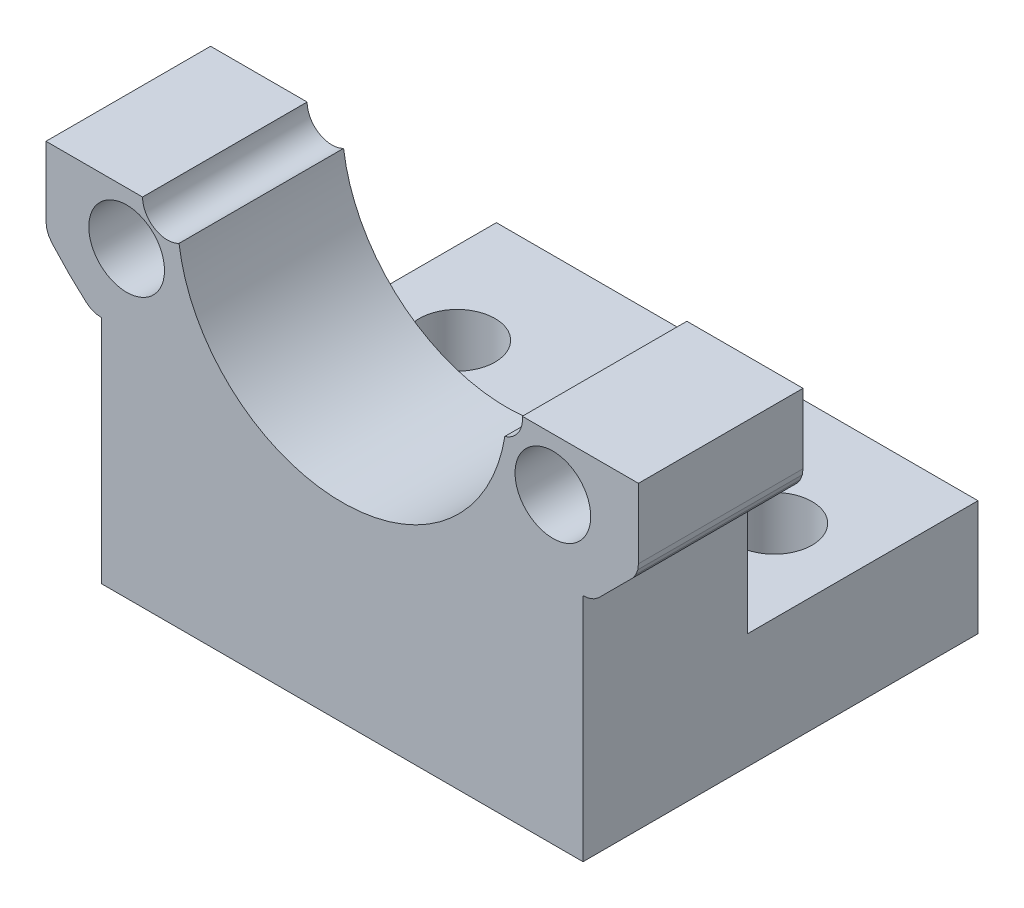
SolidWorks part; units mm, degrees
ref_plane "Front Plane" through (0, 0, 0) normal (0, 0, 1) x (1, 0, 0)
ref_plane "Top Plane" through (0, 0, 0) normal (0, 1, 0) x (1, 0, 0)
ref_plane "Right Plane" through (0, 0, 0) normal (1, 0, 0) x (0, 0, -1)
sketch "Sketch1" plane through (0, 0, 0) normal (0, 0, 1) x (1, 0, 0)
  line L1 (189.1991, 129.3361) -> (189.2194, 129.1684)
  line L2 (189.2194, 129.1684) -> (189.2766, 129.015)
  line L3 (189.2766, 129.015) -> (189.3751, 128.8705)
  line L4 (189.3751, 128.8705) -> (189.8798, 128.3332)
  line L5 (189.8798, 128.3332) -> (190.4171, 127.8285)
  line L6 (190.4171, 127.8285) -> (190.5582, 127.7318)
  line L7 (190.5582, 127.7318) -> (190.7157, 127.6726)
  line L8 (190.7157, 127.6726) -> (190.8827, 127.6526)
  line L9 (190.8827, 127.6526) -> (205.5156, 127.6526)
  line L10 (205.5156, 127.6526) -> (205.6833, 127.6728)
  line L11 (205.6833, 127.6728) -> (205.8401, 127.7318)
  line L12 (205.8401, 127.7318) -> (205.9812, 127.8285)
  line L13 (205.9812, 127.8285) -> (207.0232, 128.8705)
  line L14 (207.0232, 128.8705) -> (207.1185, 129.009)
  line L15 (207.1185, 129.009) -> (207.1789, 129.1684)
  line L16 (207.1789, 129.1684) -> (207.1991, 129.3361)
  line L17 (207.1991, 129.3361) -> (207.1991, 132.202)
  line L19 (207.1991, 132.202) -> (189.1991, 132.202)
  line L21 (189.1991, 132.202) -> (189.1991, 129.3361)
  dimension "D1" = 18
extrude "Face " add sketch "Sketch1" along normal blind 5
sketch "Sketch2" plane through (0, 127.6526, 0) normal (0, -1, 0) x (1, 0, 0)
  line L0 (55, 0) -> (-55, 0) construction
  line L1 (205.5156, 0) -> (190.8827, 0)
  line L2 (205.5156, 0) -> (205.5156, 5)
  line L3 (205.5156, 5) -> (190.8827, 5)
  line L4 (190.8827, 0) -> (190.8827, 5)
  line L5 (205.5156, 5) -> (205.5156, 0) construction
extrude "Boss-Extrude2" add sketch "Sketch2" along normal blind 7
sketch "Sketch3" plane through (0, 0, 0) normal (0, 0, -1) x (-1, 0, 0)
  line L0 (-205.5156, 127.6526) -> (-190.8827, 127.6526)
  line L1 (-190.8827, 127.6526) -> (-190.8827, 120.6526)
  line L2 (-190.8827, 120.6526) -> (-205.5156, 120.6526)
  line L3 (-205.5156, 120.6526) -> (-205.5156, 127.6526)
extrude "Boss-Extrude3" add sketch "Sketch3" along normal blind 7
sketch "Sketch4" plane through (0, 0, 5) normal (0, 0, 1) x (1, 0, 0)
  line L1 (207.1991, 132.202) -> (189.1991, 132.202) construction
  line L7 (190.4991, 129.852) -> (189.1991, 129.852) construction
  line L8 (189.1991, 132.202) -> (189.1991, 129.3361) construction
  line L9 (205.7491, 129.852) -> (207.1991, 129.852) construction
  line L10 (207.1991, 129.3361) -> (207.1991, 132.202) construction
  circle A0 centre (191.6491, 129.852) radius 1.15
  circle A1 centre (204.5991, 129.852) radius 1.15
  dimension "D5" = 2.3
  dimension "D1" = 1.3
  dimension "D2" = 1.45
  dimension "D3" = 2.35
extrude "Eye Holes" cut sketch "Sketch4" against normal up to next
sketch "Sketch5" plane through (0, 0, -7) normal (0, 0, -1) x (-1, 0, 0)
  line L0 (-205.5156, 124.1526) -> (-190.8827, 124.1526)
  line L1 (-205.5156, 127.6526) -> (-205.5156, 120.6526) construction
  line L2 (-190.8827, 120.6526) -> (-190.8827, 127.6526) construction
  line L3 (-190.8827, 124.1526) -> (-190.8827, 127.6526)
  line L4 (-190.8827, 127.6526) -> (-205.5156, 127.6526)
  line L5 (-205.5156, 127.6526) -> (-205.5156, 124.1526)
  dimension "D1" = 3.5
extrude "Seat" cut sketch "Sketch5" against normal blind 7
sketch "Sketch6" plane through (0, 132.202, 0) normal (0, 1, 0) x (1, 0, 0)
  line L1 (189.1991, 0) -> (207.1991, 0)
  line L2 (189.1991, 0) -> (189.1991, -5)
  line L3 (189.1991, -5) -> (207.1991, -5)
  line L4 (207.1991, 0) -> (207.1991, -5)
extrude "Boss-Extrude4" add sketch "Sketch6" along normal blind 3.5
sketch "Sketch7" plane through (0, 0, 5) normal (0, 0, 1) x (1, 0, 0)
  line L0 (189.1991, 135.702) -> (189.1817, 135.702) construction
  line L19 (189.1991, 135.702) -> (207.1991, 135.702) construction
  line L20 (207.1991, 135.702) -> (207.2067, 135.702) construction
  line L22 (189.1817, 135.702) -> (207.2067, 135.702)
  line L23 (189.1817, 135.702) -> (189.1817, 131.452)
  line L24 (189.1817, 131.452) -> (207.2067, 131.452)
  line L25 (207.2067, 135.702) -> (207.2067, 131.452)
  circle A1 centre (191.6491, 129.852) radius 1.15 construction
  dimension "D1" = 1.6
extrude "Top Hole" cut sketch "Sketch7" against normal through all
sketch "Sketch8" plane through (0, 0, 5) normal (0, 0, 1) x (1, 0, 0)
  line L1 (189.1991, 131.452) -> (207.1991, 131.452) construction
  circle A0 centre (198.1991, 131.452) radius 5.0037
extrude "Middle Hole" cut sketch "Sketch8" against normal through all both and the other way through all
sketch "Sketch10" plane through (0, 120.6526, 0) normal (0, -1, 0) x (1, 0, 0)
  line L0 (190.8827, 5) -> (190.8827, -7) construction
  line L1 (205.5156, -7) -> (205.5156, 5) construction
  circle A0 centre (193.3827, -3.3083) radius 1.15
  circle A1 centre (203.0156, -3.3083) radius 1.15
  dimension "D3" = 2.5
  dimension "D1" = 2.3
  dimension "D2" = 2.5
extrude "Cut-Extrude8" cut sketch "Sketch10" against normal up to surface (3.5 mm away) and the other way through all up to face at (198.1991, 124.1526, -3.5)
sketch "Sketch11" plane through (0, 0, 5) normal (0, 0, 1) x (1, 0, 0)
  line L5 (189.1991, 131.452) -> (193.1954, 131.452) construction
  circle A0 centre (192.8869, 131.452) radius 0.7544
  circle A1 centre (202.92, 131.3773) radius 0.7544
extrude "Cut-Extrude9" cut sketch "Sketch11" against normal through all
